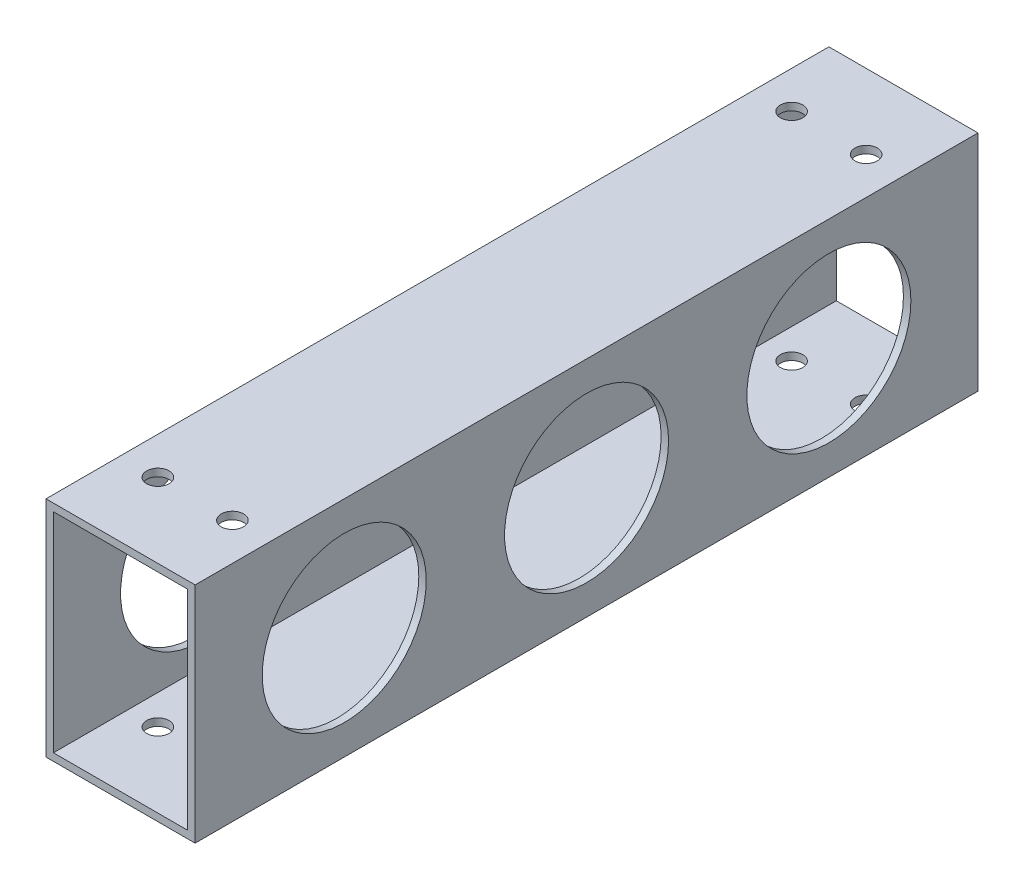
SolidWorks part; units mm, degrees
material "6061-T4 (SS)"
ref_plane "前视基准面" through (0, 0, 0) normal (0, 0, 1) x (1, 0, 0)
ref_plane "上视基准面" through (0, 0, 0) normal (0, 1, 0) x (1, 0, 0)
ref_plane "右视基准面" through (0, 0, 0) normal (1, 0, 0) x (0, 0, -1)
other "Configuration Table"
sketch "草图1" plane through (0, 0, 0) normal (0, 0, 1) x (1, 0, 0)
  line L1 (-10, -15) -> (10, -15)
  line L2 (-10, -15) -> (-10, 15)
  line L3 (-10, 15) -> (10, 15)
  line L4 (10, -15) -> (10, 15)
  line L5 (-10, -15) -> (10, 15) construction
  line L6 (-10, 15) -> (10, -15) construction
  point P0 (0, 0)
  dimension "D1" = 20
  dimension "D2" = 30
extrude "拉伸-薄壁1" add sketch "草图1" along normal blind 105 thin thin type one direction reverse wall 1
sketch "草图2" plane through (0, 15, 0) normal (0, 1, 0) x (1, 0, 0)
  line L0 (-10, -52.5) -> (0, -52.5) construction
  line L1 (-10, -105) -> (-10, 0) construction
  line L2 (10, -105) -> (-10, -105) construction
  line L3 (-5, -95) -> (5, -95) construction
  line L4 (-5, -95) -> (-5, -10) construction
  line L5 (-5, -10) -> (5, -10) construction
  line L6 (5, -95) -> (5, -10) construction
  line L7 (-5, -95) -> (5, -10) construction
  line L8 (-5, -10) -> (5, -95) construction
  circle A0 centre (5, -10) radius 1.5
  circle A1 centre (-5, -10) radius 1.5
  circle A2 centre (5, -95) radius 1.5
  circle A3 centre (-5, -95) radius 1.5
  dimension "D3" = 3
  dimension "D1" = 10
  dimension "D2" = 10
  dimension "D4" = 10
extrude "切除-拉伸1" cut sketch "草图2" against normal up to surface (30 mm away) up to face at (0, -15, 52.5)
sketch "草图5" plane through (10, 0, 0) normal (1, 0, 0) x (0, 0, -1)
  line L0 (-105, 0) -> (-85, 0) construction
  line L1 (-105, -15) -> (-105, 15) construction
  line L2 (-85, 0) -> (-52.5, 0) construction
  line L3 (-52.5, 0) -> (-20, 0) construction
  line L4 (-20, 0) -> (0, 0) construction
  circle A1 centre (-20, 0) radius 11
  circle A2 centre (-52.5, 0) radius 11
  circle A3 centre (-85, 0) radius 11
  dimension "D3" = 22
  dimension "D4" = 32.5
  dimension "D1" = 20
  dimension "D2" = 20
extrude "切除-拉伸3" cut sketch "草图5" against normal up to surface (20 mm away) up to face at (-10, 0, 52.5)
